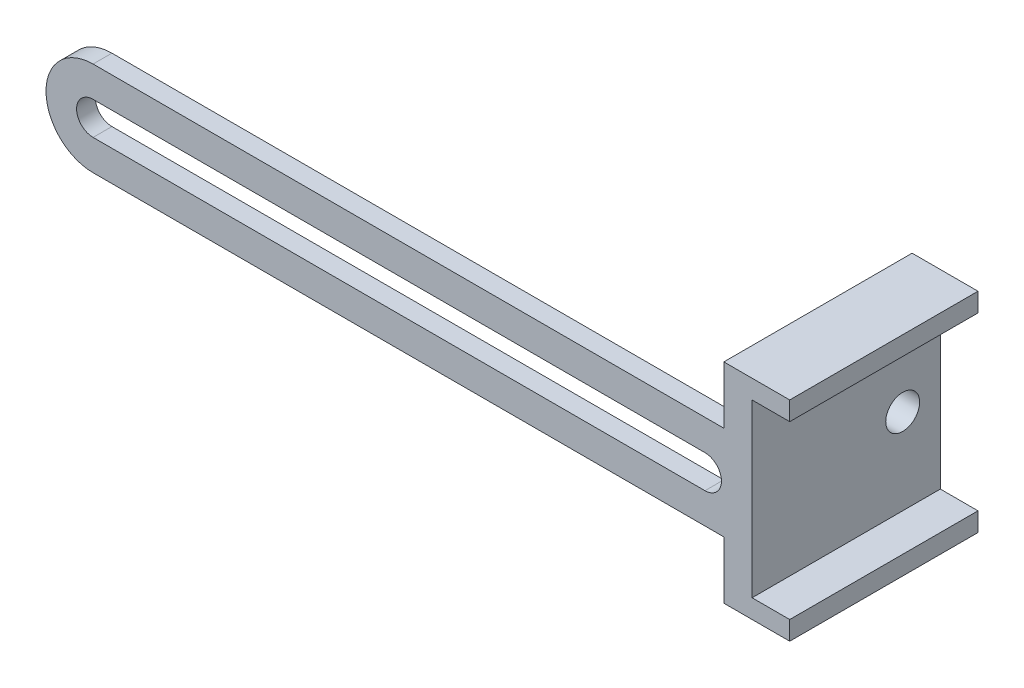
SolidWorks part; units mm, degrees
ref_plane "Front Plane" through (0, 0, 0) normal (0, 0, 1) x (1, 0, 0)
ref_plane "Top Plane" through (0, 0, 0) normal (0, 1, 0) x (1, 0, 0)
ref_plane "Right Plane" through (0, 0, 0) normal (1, 0, 0) x (0, 0, -1)
sketch "Sketch1" plane through (0, 0, 0) normal (0, 0, 1) x (1, 0, 0)
  line L0 (0, 0) -> (65, 0) construction
  line L1 (0, 1.75) -> (65, 1.75)
  line L2 (0, -1.75) -> (65, -1.75)
  line L3 (0, 0) -> (72.7097, 0) construction
  line L4 (0, 5) -> (70, 5)
  line L5 (0, -5) -> (70, -5)
  line L6 (70, 5) -> (70, -5)
  arc A0 (0, 1.75) -> (0, -1.75) centre (0, 0) ccw
  arc A1 (65, -1.75) -> (65, 1.75) centre (65, 0) ccw
  arc A2 (0, 5) -> (0, -5) centre (0, 0) ccw
  point P3 (32.5, 0)
  point P10 (36.3548, 0)
  dimension "D1" = 3.5
  dimension "D2" = 65
  dimension "D3" = 10
  dimension "D5" = 5
  dimension "D6" = 5
extrude "Boss-Extrude1" add sketch "Sketch1" against normal blind 2
sketch "Sketch2" plane through (0, 0, 0) normal (0, 0, 1) x (1, 0, 0)
  line L0 (74, 11.1) -> (67, 11.1)
  line L3 (67, 11.1) -> (67, -11.1)
  line L4 (74, -11.1) -> (74, -9.1)
  line L5 (74, -9.1) -> (70, -9.1)
  line L6 (70, -5) -> (70, 5) construction
  line L7 (70, -9.1) -> (70, 9.1)
  line L8 (70, 9.1) -> (74, 9.1)
  line L9 (74, 9.1) -> (74, 11.1)
  line L10 (67, -11.1) -> (74, -11.1)
  line L11 (74, 9.1) -> (74, -11.1) construction
  line L12 (0, 0) -> (100.3164, 0) construction
  dimension "D1" = 3
  dimension "D2" = 4
  dimension "D3" = 18.2
  dimension "D4" = 9.1
  dimension "D5" = 2
  dimension "D6" = 2
extrude "Boss-Extrude2" add sketch "Sketch2" against normal blind 20
sketch "Sketch3" plane through (67, 0, 0) normal (-1, 0, 0) x (0, 0, 1)
  line L0 (0, 0) -> (-17.5777, 0) construction
  line L2 (-20, 11.1) -> (-20, -11.1) construction
  circle A0 centre (-16, 0) radius 1.8
  dimension "D1" = 3.6
  dimension "D2" = 4
extrude "Cut-Extrude1" cut sketch "Sketch3" against normal blind 15
equation "\"D5@Sketch1\"=\"D3@Sketch1\"/2"
equation "\"D4@Sketch2\"=\"D3@Sketch2\"/2"
